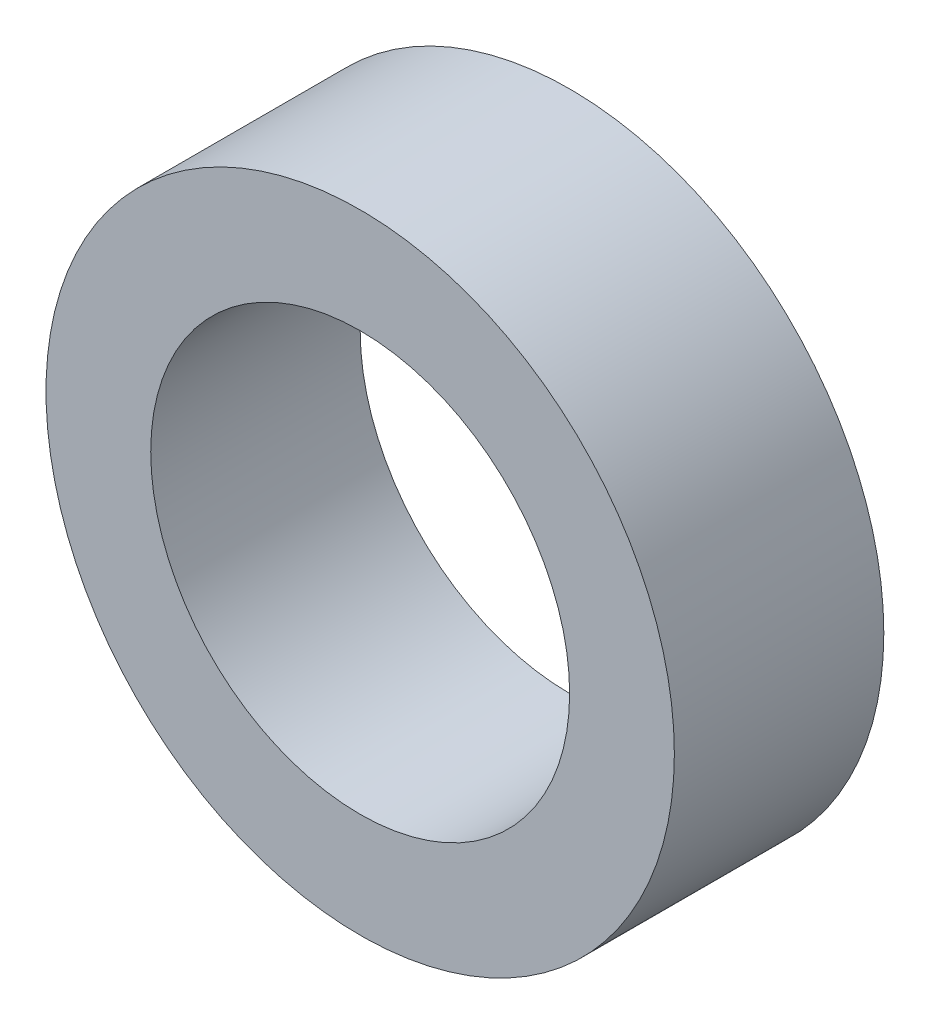
SolidWorks part; units mm, degrees
ref_plane "Front Plane" through (0, 0, 0) normal (0, 0, 1) x (1, 0, 0)
ref_plane "Top Plane" through (0, 0, 0) normal (0, 1, 0) x (1, 0, 0)
ref_plane "Right Plane" through (0, 0, 0) normal (1, 0, 0) x (0, 0, -1)
sketch "Sketch1" plane through (0, 0, 0) normal (0, 0, 1) x (1, 0, 0)
  circle A0 centre (0, 0) radius 4.7625
  circle A1 centre (0, 0) radius 3.175
extrude "Boss-Extrude1" add sketch "Sketch1" along normal blind 3.175
